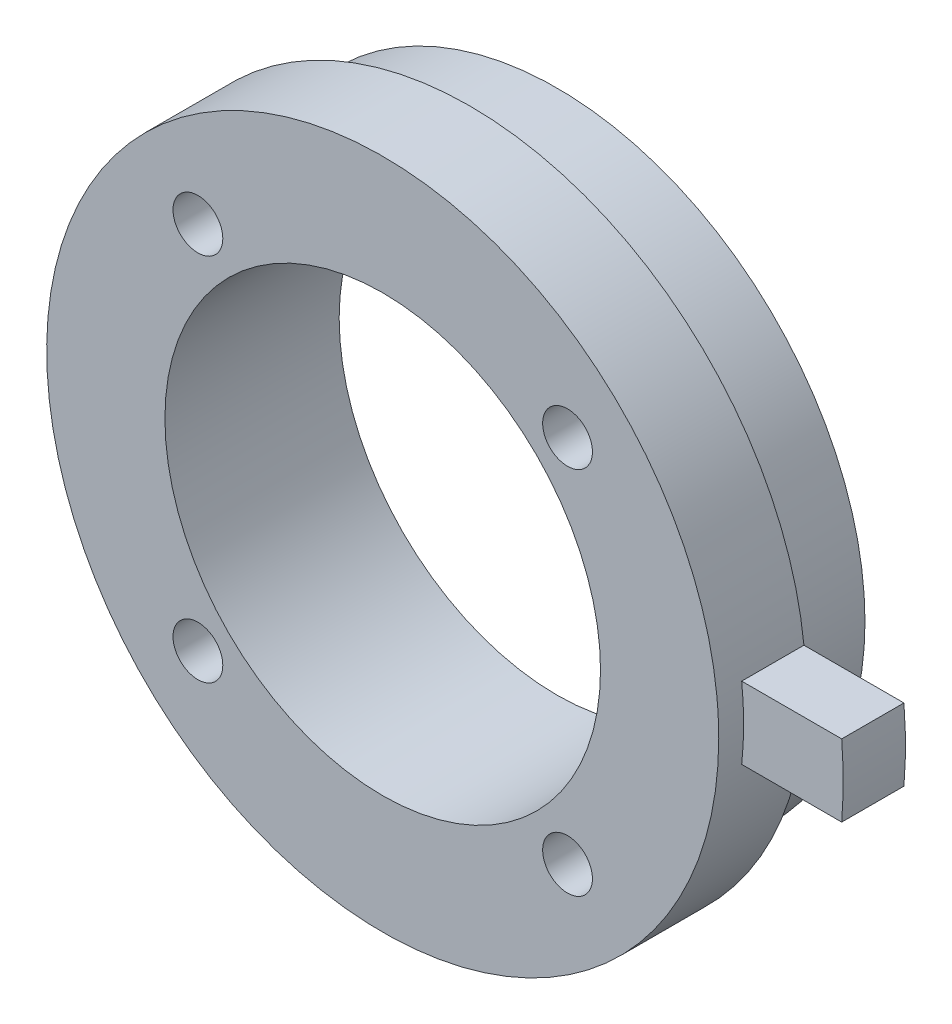
SolidWorks part; units mm, degrees
ref_plane "前视基准面" through (0, 0, 0) normal (0, 0, 1) x (1, 0, 0)
ref_plane "上视基准面" through (0, 0, 0) normal (0, 1, 0) x (1, 0, 0)
ref_plane "右视基准面" through (0, 0, 0) normal (1, 0, 0) x (0, 0, -1)
other "Configuration Table"
sketch "草图1" plane through (0, 0, 0) normal (0, 0, 1) x (1, 0, 0)
  circle A0 centre (0, 0) radius 24.75
  circle A1 centre (0, 0) radius 17.5
  dimension "D1" = 49.5
  dimension "D2" = 35
extrude "凸台-拉伸1" add sketch "草图1" along normal mid plane 7
sketch "草图2" plane through (0, 0, 3.5) normal (0, 0, 1) x (1, 0, 0)
  circle A0 centre (0, 0) radius 17.5 construction
  circle A1 centre (0, 0) radius 17.5
  circle A2 centre (0, 0) radius 27
  dimension "D1" = 54
extrude "凸台-拉伸2" add sketch "草图2" along normal blind 7
sketch "草图3" plane through (0, 0, -3.5) normal (0, 0, -1) x (-1, 0, 0)
  line L1 (-14.8492, 14.8492) -> (14.8492, 14.8492) construction
  line L2 (-14.8492, 14.8492) -> (-14.8492, -14.8492) construction
  line L3 (-14.8492, -14.8492) -> (14.8492, -14.8492) construction
  line L4 (14.8492, 14.8492) -> (14.8492, -14.8492) construction
  line L5 (-14.8492, 14.8492) -> (14.8492, -14.8492) construction
  line L6 (-14.8492, -14.8492) -> (14.8492, 14.8492) construction
  circle A0 centre (14.8492, 14.8492) radius 2
  circle A1 centre (14.8492, -14.8492) radius 2
  circle A2 centre (-14.8492, -14.8492) radius 2
  circle A3 centre (-14.8492, 14.8492) radius 2
  point P0 (0, 0)
  dimension "D2" = 4
  dimension "D3" = 4
  dimension "D4" = 4
  dimension "D5" = 4
  dimension "D1" = 42
extrude "切除-拉伸1" cut sketch "草图3" against normal blind 15
sketch "草图4" plane through (0, 0, 3.5) normal (0, 0, -1) x (-1, 0, 0)
  line L0 (-34.88, 2.8961) -> (-24.58, 2.8961)
  line L1 (-34.88, -2.8961) -> (-24.58, -2.8961)
  arc A0 (-34.88, 2.8961) -> (-34.88, -2.8961) centre (0, 0) ccw
  circle A1 centre (0, 0) radius 24.75 construction
  circle A2 centre (0, 0) radius 24.75 construction
  circle A3 centre (0, 0) radius 24.75
  circle M3 centre (0, 0) radius 24.75
  circle M4 centre (0, 0) radius 27
  dimension "D1" = 35
  dimension "D2" = 10.3
extrude "凸台-拉伸3" add sketch "草图4" against normal blind 5 contours L1 L0 M4 M3 | L0 A0 L1 M4
